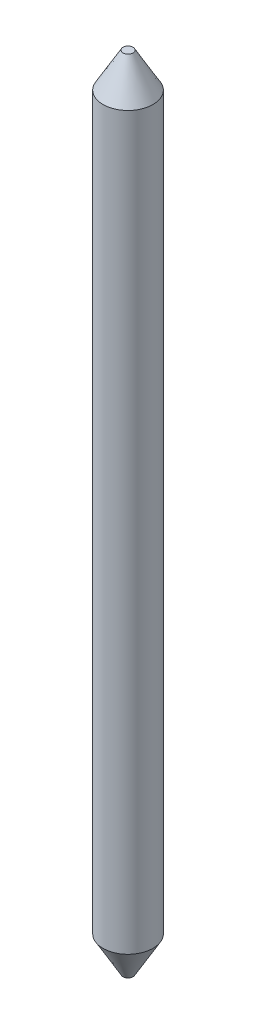
SolidWorks part; units mm, degrees
material "Custom Plastic"
ref_plane "Front Plane" through (0, 0, 0) normal (0, 0, 1) x (1, 0, 0)
ref_plane "Top Plane" through (0, 0, 0) normal (0, 1, 0) x (1, 0, 0)
ref_plane "Right Plane" through (0, 0, 0) normal (1, 0, 0) x (0, 0, -1)
sketch "Sketch1" plane through (0, 0, 0) normal (0, 1, 0) x (1, 0, 0)
  circle A0 centre (0, 0) radius 3.175
  dimension "D1" = 6.35
extrude "Boss-Extrude1" add sketch "Sketch1" along normal blind 101.6
sketch "Sketch3" plane through (0, 0, 0) normal (0, 0, 1) x (1, 0, 0)
  line L0 (0, 101.6) -> (0, 0) construction
  line L1 (3.175, 101.6) -> (-3.175, 101.6) construction
  line L2 (3.175, 97.2006) -> (0.635, 101.6)
  line L3 (3.175, 0) -> (3.175, 101.6) construction
  line L4 (3.175, 97.2006) -> (3.175, 101.6)
  line L5 (3.175, 101.6) -> (0.635, 101.6)
  dimension "D1" = 1.27
  dimension "D2" = 30
revolve "Cut-Revolve2" cut sketch "Sketch3" angle 360 about L0
ref_plane "Plane1" through (0, 50.8, 0) normal (0, 1, 0) x (1, 0, 0)
mirror "Mirror1" about plane through (0, 50.8, 0) normal (0, 1, 0) of "Cut-Revolve2"
